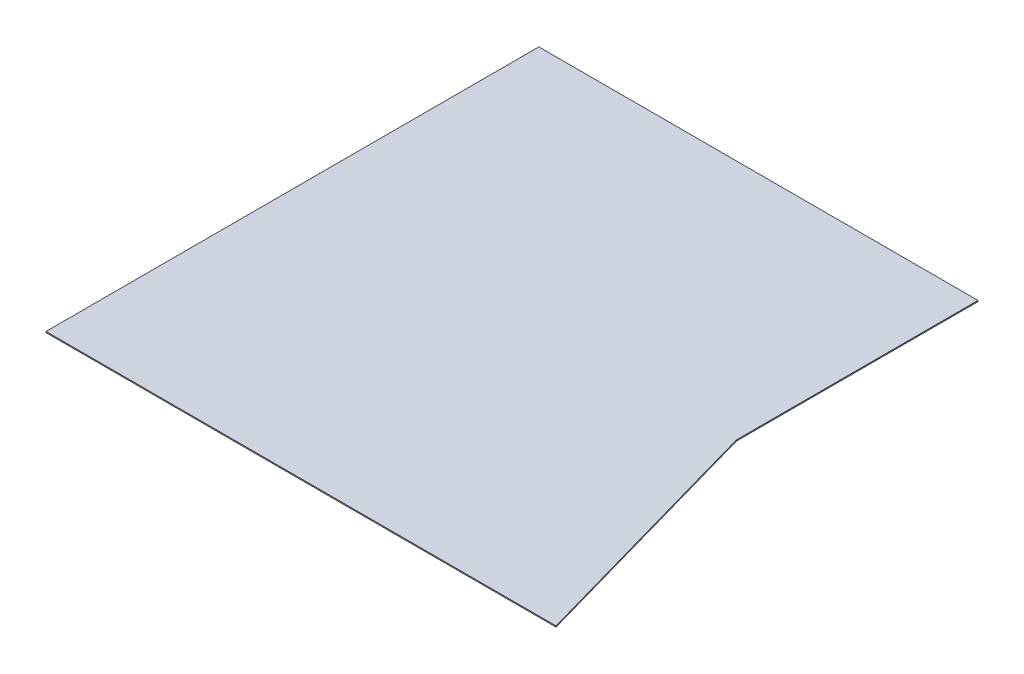
SolidWorks part; units mm, degrees
ref_plane "前视基准面" through (0, 0, 0) normal (0, 0, 1) x (1, 0, 0)
ref_plane "上视基准面" through (0, 0, 0) normal (0, 1, 0) x (1, 0, 0)
ref_plane "右视基准面" through (0, 0, 0) normal (1, 0, 0) x (0, 0, -1)
sketch "草图1" plane through (0, 0, 0) normal (0, 1, 0) x (1, 0, 0)
  line L0 (418.4502, 85.999) -> (418.4502, -364.001)
  line L1 (-399.5498, 85.999) -> (418.4502, 85.999)
  line L2 (-399.5498, 85.999) -> (-399.5498, -832.001)
  line L3 (-399.5498, -832.001) -> (550.4502, -832.001)
  line L5 (418.4502, -364.001) -> (550.4502, -832.001)
  dimension "D1" = 450
  dimension "D2" = 918
  dimension "D3" = 950
  dimension "D4" = 818
extrude "凸台-拉伸1" add sketch "草图1" along normal blind 2
